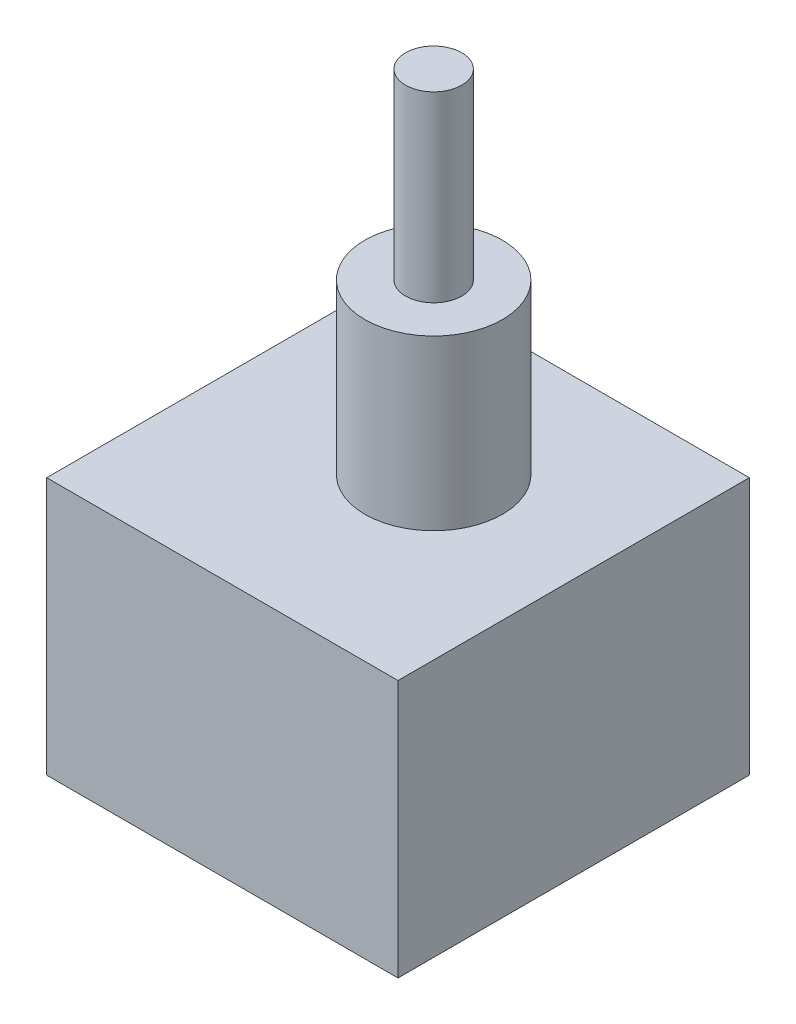
SolidWorks part; units mm, degrees
ref_plane "Спереди" through (0, 0, 0) normal (0, 0, 1) x (1, 0, 0)
ref_plane "Сверху" through (0, 0, 0) normal (0, 1, 0) x (1, 0, 0)
ref_plane "Справа" through (0, 0, 0) normal (1, 0, 0) x (0, 0, -1)
other "Configuration Table"
sketch "Эскиз1" plane through (0, 0, 0) normal (0, 1, 0) x (1, 0, 0)
  line L1 (-16.2944, 13.2487) -> (13.7056, 13.2487)
  line L2 (-16.2944, 13.2487) -> (-16.2944, -16.7513)
  line L3 (-16.2944, -16.7513) -> (13.7056, -16.7513)
  line L4 (13.7056, 13.2487) -> (13.7056, -16.7513)
  dimension "D1" = 30
  dimension "D2" = 30
extrude "высота " add sketch "Эскиз1" along normal blind 22
sketch "Эскиз2" plane through (0, 22, 0) normal (0, 1, 0) x (1, 0, 0)
  circle A0 centre (0, 0) radius 5.875
  dimension "D1" = 11.75
sketch "Эскиз3" plane through (0, 0, 0) normal (0, 0, 1) x (1, 0, 0)
  line L0 (0, 49.97) -> (0, -1.7648) construction
extrude "Бобышка-Вытянуть2" add sketch "Эскиз2" along normal blind 14.4 contours A0
sketch "Эскиз4" plane through (0, 36.4, 0) normal (0, 1, 0) x (1, 0, 0)
  circle A0 centre (0, 0) radius 2.4
  dimension "D1" = 4.8
extrude "Бобышка-Вытянуть3" add sketch "Эскиз4" along normal blind 15.6
